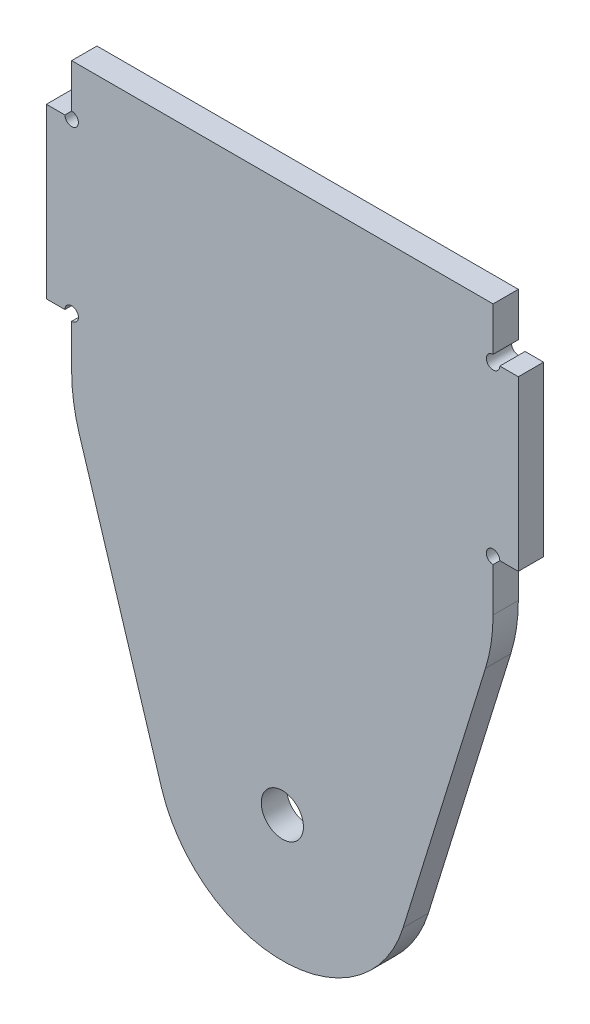
SolidWorks part; units mm, degrees
material "Thornel Mat VMA"
ref_plane "Front Plane" through (0, 0, 0) normal (0, 0, 1) x (1, 0, 0)
ref_plane "Top Plane" through (0, 0, 0) normal (0, 1, 0) x (1, 0, 0)
ref_plane "Right Plane" through (0, 0, 0) normal (1, 0, 0) x (0, 0, -1)
sketch "Sketch1" plane through (0, 0, 0) normal (0, 0, 1) x (1, 0, 0)
  line L1 (-25, -17.5) -> (25, -17.5)
  line L2 (-25, -17.5) -> (-25, 17.5)
  line L3 (-25, 17.5) -> (25, 17.5)
  line L4 (25, -17.5) -> (25, 17.5)
  line L5 (-25, -17.5) -> (25, 17.5) construction
  line L6 (-25, 17.5) -> (25, -17.5) construction
  line L7 (0, -17.5) -> (0, -47.5) construction
  line L8 (-25, -17.5) -> (-14.3279, -51.9399)
  line L9 (25, -17.5) -> (14.3279, -51.9399)
  arc A0 (-14.3279, -51.9399) -> (14.3279, -51.9399) centre (0, -47.5) ccw
  circle A1 centre (0, -47.5) radius 2.5
  point P0 (0, 0)
  dimension "D3" = 15
  dimension "D4" = 5
  dimension "D1" = 50
  dimension "D2" = 35
  dimension "D5" = 30
extrude "Boss-Extrude1" add sketch "Sketch1" along normal blind 3 contours L1 L4 L3 L2 | L8 A0 L9 L1 A1
fillet "Fillet1" radius 20 2 edges at (-25, -17.5, 1.5) (25, -17.5, 1.5)
sketch "Sketch2" plane through (0, 0, 3) normal (0, 0, 1) x (1, 0, 0)
  line L0 (-25, -14.4722) -> (-25, 17.5) construction
  line L1 (-28, -8.4861) -> (-22, -8.4861)
  line L2 (-28, -8.4861) -> (-28, 11.5139)
  line L3 (-28, 11.5139) -> (-22, 11.5139)
  line L4 (-22, -8.4861) -> (-22, 11.5139)
  line L5 (-28, -8.4861) -> (-22, 11.5139) construction
  line L6 (-28, 11.5139) -> (-22, -8.4861) construction
  line L7 (0, 0) -> (0, 17.5) construction
  line L8 (-25, 17.5) -> (25, 17.5) construction
  line L9 (28, 11.5139) -> (22, -8.4861) construction
  line L10 (28, -8.4861) -> (22, 11.5139) construction
  line L11 (22, -8.4861) -> (22, 11.5139)
  line L12 (28, 11.5139) -> (22, 11.5139)
  line L13 (28, -8.4861) -> (28, 11.5139)
  line L14 (28, -8.4861) -> (22, -8.4861)
  point P0 (-25, 1.5139)
  point P16 (25, 1.5139)
  dimension "D1" = 6
  dimension "D2" = 20
extrude "Boss-Extrude2" add sketch "Sketch2" against normal up to surface (3 mm away) up to face at (0, -18.6545, 0)
sketch "Sketch3" plane through (0, 0, 3) normal (0, 0, 1) x (1, 0, 0)
  circle A0 centre (-25, 11.5139) radius 0.8
  circle A1 centre (-25, -8.4861) radius 0.8
  circle A2 centre (25, 11.5139) radius 0.8
  circle A3 centre (25, -8.4861) radius 0.8
  dimension "D1" = 1.6
extrude "Cut-Extrude1" cut sketch "Sketch3" against normal through all
